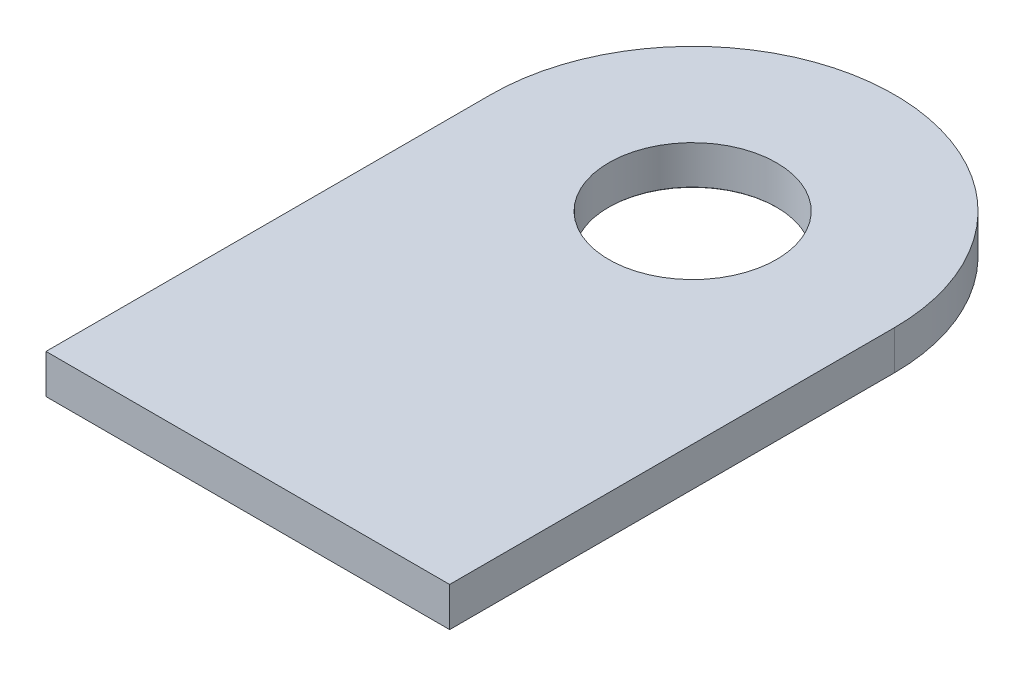
SolidWorks part; units mm, degrees
ref_plane "Front Plane" through (0, 0, 0) normal (0, 0, 1) x (1, 0, 0)
ref_plane "Top Plane" through (0, 0, 0) normal (0, 1, 0) x (1, 0, 0)
ref_plane "Right Plane" through (0, 0, 0) normal (1, 0, 0) x (0, 0, -1)
sketch "Sketch1" plane through (0, 0, 0) normal (0, 1, 0) x (1, 0, 0)
  line L0 (-7.94, 0) -> (-7.94, -17.5)
  line L1 (-7.94, -17.5) -> (7.94, -17.5)
  line L2 (7.94, -17.5) -> (7.94, 0)
  circle A0 centre (0, 0) radius 7.94
  dimension "D1" = 15.88
  dimension "D2" = 17.5
extrude "Boss-Extrude1" add sketch "Sketch1" along normal blind 1.54 contours A0 | A0 L0 L1 L2
sketch "Sketch4" plane through (0, 0, 0) normal (0, -1, 0) x (-1, 0, 0)
  point P0 (0, 0)
hole_wizard "M6 Clearance Hole1" positions "Sketch4" profile "Sketch3" hole size "M6" standard "ANSI Metric" end condition through all
sketch "Sketch3" plane through (0, 0, 0) normal (1, 0, 0) x (0, 0, -1)
  line L0 (0, 0) -> (0, 1.54)
  line L1 (0, 1.54) -> (3.3, 1.54)
  line L2 (3.3, 1.54) -> (3.3, 0.025)
  line L3 (3.3, 0.025) -> (3.325, 0)
  line L5 (3.325, 0) -> (0, 0)
  line L6 (-3.3, 0.025) -> (-3.325, 0) construction
  line L11 (0, -6.35) -> (0, 107.95) construction
  dimension "Thru Hole Dia." = 6.6
  dimension "Thru Hole Depth" = 1.54
  dimension "Near C'Sink Dia." = 6.65
  dimension "Near C'Sink Angle" = 90
